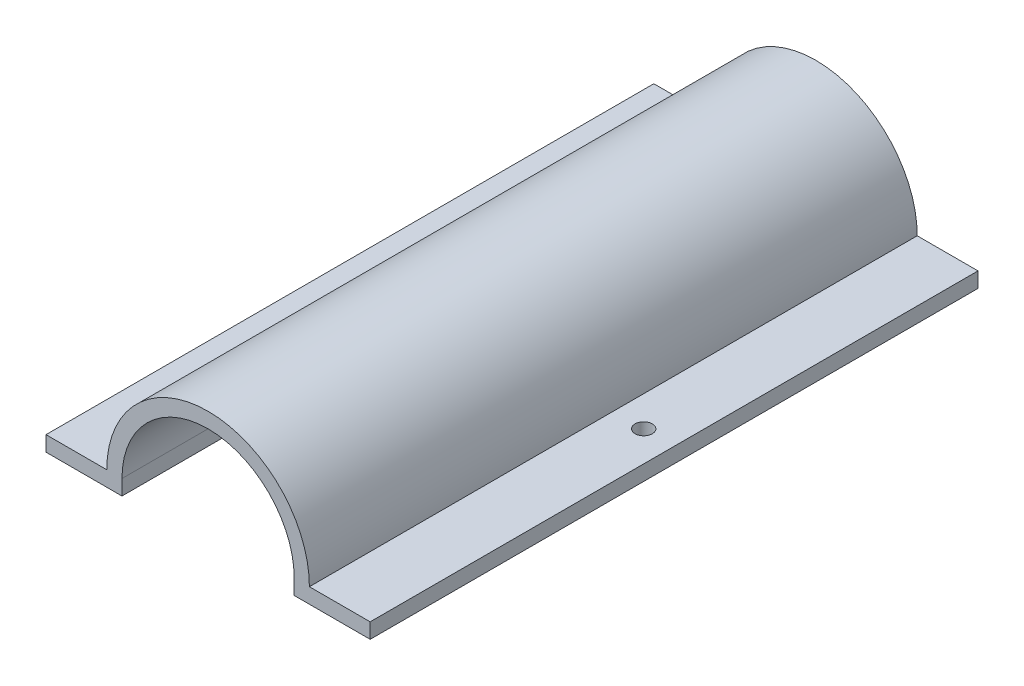
SolidWorks part; units mm, degrees
material "PMMA"
ref_plane "Ebene vorne" through (0, 0, 0) normal (0, 0, 1) x (1, 0, 0)
ref_plane "Ebene oben" through (0, 0, 0) normal (0, 1, 0) x (1, 0, 0)
ref_plane "Ebene rechts" through (0, 0, 0) normal (1, 0, 0) x (0, 0, -1)
sketch "Skizze1" plane through (0, 0, 0) normal (0, 0, 1) x (1, 0, 0)
  line L0 (0, 0) -> (15, 0)
  line L1 (49, 0) -> (64, 0)
  line L2 (64, 0) -> (64, 3)
  line L3 (64, 3) -> (52, 3)
  line L4 (12, 3) -> (0, 3)
  line L5 (0, 3) -> (0, 0)
  line L6 (15, 3) -> (15, 0)
  line L7 (49, 3) -> (49, 0)
  arc A0 (49, 3) -> (15, 3) centre (32, 3) ccw
  arc A2 (52, 3) -> (12, 3) centre (32, 3) ccw
  dimension "D1" = 20
  dimension "D2" = 17
  dimension "D3" = 12
  dimension "D4" = 12
  dimension "D5" = 3
extrude "Aufsatz-Linear austragen1" add sketch "Skizze1" along normal blind 120
hole_wizard "Ø3.4 (3.4) Durchmesser Bohrung1" positions "Skizze3" profile "Skizze2" hole size "Ø3.4" standard "DIN"
sketch "Skizze3" plane through (0, 3, 0) normal (0, 1, 0) x (1, 0, 0)
  line L4 (64, -120) -> (52, -120) construction
  line L5 (0, -120) -> (0, 0) construction
  point P0 (58, -60)
  point P2 (6, -60)
  dimension "D1" = 52
  dimension "D2" = 60
  dimension "D3" = 6
sketch "Skizze2" plane through (58, 3, 60) normal (1, 0, 0) x (0, 0, 1)
  line L0 (0, 0) -> (0, 6.0215)
  line L1 (0, 6.0215) -> (1.7, 5)
  line L2 (1.7, 5) -> (1.7, 0)
  line L5 (1.7, 0) -> (0, 0)
  line L10 (0, 6.0215) -> (-1.7, 5) construction
  line L11 (0, -6.35) -> (0, 107.95) construction
  dimension "Bohrerdurchmesser" = 3.4
  dimension "Bohrungstiefe" = 5
  dimension "Spitzenwinkel" = 118
